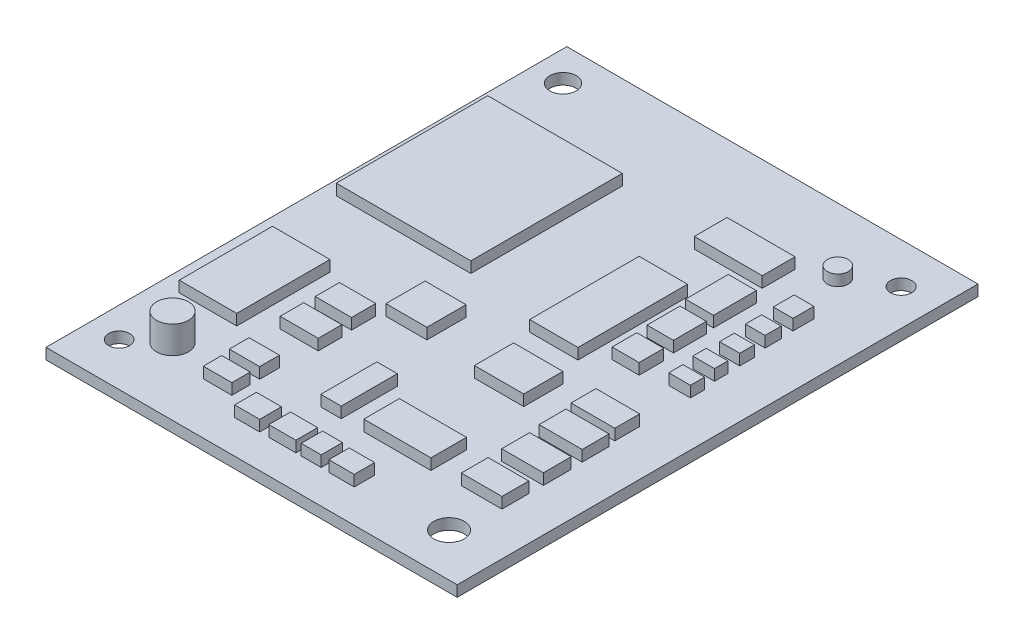
SolidWorks part; units mm, degrees
ref_plane "Front Plane" through (0, 0, 0) normal (0, 0, 1) x (1, 0, 0)
ref_plane "Top Plane" through (0, 0, 0) normal (0, 1, 0) x (1, 0, 0)
ref_plane "Right Plane" through (0, 0, 0) normal (1, 0, 0) x (0, 0, -1)
sketch "Sketch1" plane through (0, 0, 0) normal (0, 1, 0) x (1, 0, 0)
  line L1 (-15, 19) -> (15, 19)
  line L2 (-15, 19) -> (-15, -19)
  line L3 (-15, -19) -> (15, -19)
  line L4 (15, 19) -> (15, -19)
  line L5 (-15, 19) -> (15, -19) construction
  line L6 (-15, -19) -> (15, 19) construction
  point P0 (0, 0)
  dimension "D1" = 30
  dimension "D2" = 38
extrude "Boss-Extrude1" add sketch "Sketch1" along normal blind 0.8
sketch "Sketch2" plane through (0, 0.8, 0) normal (0, 1, 0) x (1, 0, 0)
  circle A0 centre (11.2507, -15.8422) radius 1.1091
  circle A1 centre (-12.8224, -15.8422) radius 0.767
  circle A2 centre (12.3598, 16.0288) radius 0.7754
  circle A3 centre (-12.8224, 16.5455) radius 0.9653
extrude "Cut-Extrude1" cut sketch "Sketch2" against normal blind 0.8
sketch "Sketch3" plane through (0, 0.8, 0) normal (0, 1, 0) x (1, 0, 0)
  line L1 (1.93, -10.1482) -> (6.8248, -10.1482)
  line L2 (1.93, -10.1482) -> (1.93, -12.7419)
  line L3 (1.93, -12.7419) -> (6.8248, -12.7419)
  line L4 (6.8248, -10.1482) -> (6.8248, -12.7419)
  line L5 (1.93, -10.1482) -> (6.8248, -12.7419) construction
  line L6 (1.93, -12.7419) -> (6.8248, -10.1482) construction
  line L7 (-13.5845, -3.8908) -> (-9.3917, -3.8908)
  line L8 (-13.5845, -3.8908) -> (-13.5845, -10.6955)
  line L9 (-13.5845, -10.6955) -> (-9.3917, -10.6955)
  line L10 (-9.3917, -3.8908) -> (-9.3917, -10.6955)
  line L11 (-13.5845, -3.8908) -> (-9.3917, -10.6955) construction
  line L12 (-13.5845, -10.6955) -> (-9.3917, -3.8908) construction
  line L13 (2.5786, -2.4623) -> (6.1761, -2.4623)
  line L14 (2.5786, -2.4623) -> (2.5786, -5.3193)
  line L15 (2.5786, -5.3193) -> (6.1761, -5.3193)
  line L16 (6.1761, -2.4623) -> (6.1761, -5.3193)
  line L17 (2.5786, -2.4623) -> (6.1761, -5.3193) construction
  line L18 (2.5786, -5.3193) -> (6.1761, -2.4623) construction
  line L19 (1.6859, 7.5904) -> (5.2143, 7.5904)
  line L20 (1.6859, 7.5904) -> (1.6859, -0.3999)
  line L21 (1.6859, -0.3999) -> (5.2143, -0.3999)
  line L22 (5.2143, 7.5904) -> (5.2143, -0.3999)
  line L23 (1.6859, 7.5904) -> (5.2143, -0.3999) construction
  line L24 (1.6859, -0.3999) -> (5.2143, 7.5904) construction
  line L25 (2.4412, 13.249) -> (7.4016, 13.249)
  line L26 (2.4412, 13.249) -> (2.4412, 10.857)
  line L27 (2.4412, 10.857) -> (7.4016, 10.857)
  line L28 (7.4016, 13.249) -> (7.4016, 10.857)
  line L29 (2.4412, 13.249) -> (7.4016, 10.857) construction
  line L30 (2.4412, 10.857) -> (7.4016, 13.249) construction
  line L31 (-7.5907, -5.0005) -> (-4.9407, -5.0005)
  line L32 (-7.5907, -5.0005) -> (-7.5907, -6.7672)
  line L33 (-7.5907, -6.7672) -> (-4.9407, -6.7672)
  line L34 (-4.9407, -5.0005) -> (-4.9407, -6.7672)
  line L35 (-7.5907, -5.0005) -> (-4.9407, -6.7672) construction
  line L36 (-7.5907, -6.7672) -> (-4.9407, -5.0005) construction
  line L37 (-7.6193, -7.5766) -> (-4.841, -7.5766)
  line L38 (-7.6193, -7.5766) -> (-7.6193, -9.2961)
  line L39 (-7.6193, -9.2961) -> (-4.841, -9.2961)
  line L40 (-4.841, -7.5766) -> (-4.841, -9.2961)
  line L41 (-7.6193, -7.5766) -> (-4.841, -9.2961) construction
  line L42 (-7.6193, -9.2961) -> (-4.841, -7.5766) construction
  line L43 (-1.2109, -8.6492) -> (0.2813, -8.6492)
  line L44 (-1.2109, -8.6492) -> (-1.2109, -12.7419)
  line L45 (-1.2109, -12.7419) -> (0.2813, -12.7419)
  line L46 (0.2813, -8.6492) -> (0.2813, -12.7419)
  line L47 (-1.2109, -8.6492) -> (0.2813, -12.7419) construction
  line L48 (-1.2109, -12.7419) -> (0.2813, -8.6492) construction
  line L49 (-7.4035, -11.7825) -> (-5.189, -11.7825)
  line L50 (-7.4035, -11.7825) -> (-7.4035, -13.2229)
  line L51 (-7.4035, -13.2229) -> (-5.189, -13.2229)
  line L52 (-5.189, -11.7825) -> (-5.189, -13.2229)
  line L53 (-7.4035, -11.7825) -> (-5.189, -13.2229) construction
  line L54 (-7.4035, -13.2229) -> (-5.189, -11.7825) construction
  line L55 (-7.2713, -13.9088) -> (-5.189, -13.9088)
  line L56 (-7.2713, -13.9088) -> (-7.2713, -15.2524)
  line L57 (-7.2713, -15.2524) -> (-5.189, -15.2524)
  line L58 (-5.189, -13.9088) -> (-5.189, -15.2524)
  line L59 (-7.2713, -13.9088) -> (-5.189, -15.2524) construction
  line L60 (-7.2713, -15.2524) -> (-5.189, -13.9088) construction
  line L61 (8.8919, -10.6347) -> (11.8568, -10.6347)
  line L62 (8.8919, -10.6347) -> (8.8919, -12.5892)
  line L63 (8.8919, -12.5892) -> (11.8568, -12.5892)
  line L64 (11.8568, -10.6347) -> (11.8568, -12.5892)
  line L65 (8.8919, -10.6347) -> (11.8568, -12.5892) construction
  line L66 (8.8919, -12.5892) -> (11.8568, -10.6347) construction
  line L67 (8.832, -7.5502) -> (11.872, -7.5502)
  line L68 (8.832, -7.5502) -> (8.832, -9.5816)
  line L69 (8.832, -9.5816) -> (11.872, -9.5816)
  line L70 (11.872, -7.5502) -> (11.872, -9.5816)
  line L71 (8.832, -7.5502) -> (11.872, -9.5816) construction
  line L72 (8.832, -9.5816) -> (11.872, -7.5502) construction
  line L73 (8.6665, -4.7293) -> (11.8136, -4.7293)
  line L74 (8.6665, -4.7293) -> (8.6665, -6.6941)
  line L75 (8.6665, -6.6941) -> (11.8136, -6.6941)
  line L76 (11.8136, -4.7293) -> (11.8136, -6.6941)
  line L77 (8.6665, -4.7293) -> (11.8136, -6.6941) construction
  line L78 (8.6665, -6.6941) -> (11.8136, -4.7293) construction
  line L79 (8.4704, -2.3451) -> (11.6619, -2.3451)
  line L80 (8.4704, -2.3451) -> (8.4704, -4.1633)
  line L81 (8.4704, -4.1633) -> (11.6619, -4.1633)
  line L82 (11.6619, -2.3451) -> (11.6619, -4.1633)
  line L83 (8.4704, -2.3451) -> (11.6619, -4.1633) construction
  line L84 (8.4704, -4.1633) -> (11.6619, -2.3451) construction
  line L85 (10.1264, 2.3454) -> (11.7073, 2.3454)
  line L86 (10.1264, 2.3454) -> (10.1264, 1.3123)
  line L87 (10.1264, 1.3123) -> (11.7073, 1.3123)
  line L88 (11.7073, 2.3454) -> (11.7073, 1.3123)
  line L89 (10.1264, 2.3454) -> (11.7073, 1.3123) construction
  line L90 (10.1264, 1.3123) -> (11.7073, 2.3454) construction
  line L91 (9.9465, 4.2213) -> (11.5322, 4.2213)
  line L92 (9.9465, 4.2213) -> (9.9465, 3.2424)
  line L93 (9.9465, 3.2424) -> (11.5322, 3.2424)
  line L94 (11.5322, 4.2213) -> (11.5322, 3.2424)
  line L95 (9.9465, 4.2213) -> (11.5322, 3.2424) construction
  line L96 (9.9465, 3.2424) -> (11.5322, 4.2213) construction
  line L97 (10.0141, 6.2043) -> (11.4835, 6.2043)
  line L98 (10.0141, 6.2043) -> (10.0141, 5.1318)
  line L99 (10.0141, 5.1318) -> (11.4835, 5.1318)
  line L100 (11.4835, 6.2043) -> (11.4835, 5.1318)
  line L101 (10.0141, 6.2043) -> (11.4835, 5.1318) construction
  line L102 (10.0141, 5.1318) -> (11.4835, 6.2043) construction
  line L103 (9.8442, 8.3653) -> (11.2807, 8.3653)
  line L104 (9.8442, 8.3653) -> (9.8442, 7.1841)
  line L105 (9.8442, 7.1841) -> (11.2807, 7.1841)
  line L106 (11.2807, 8.3653) -> (11.2807, 7.1841)
  line L107 (9.8442, 8.3653) -> (11.2807, 7.1841) construction
  line L108 (9.8442, 7.1841) -> (11.2807, 8.3653) construction
  line L109 (9.7825, 10.8031) -> (11.2191, 10.8031)
  line L110 (9.7825, 10.8031) -> (9.7825, 9.2813)
  line L111 (9.7825, 9.2813) -> (11.2191, 9.2813)
  line L112 (11.2191, 10.8031) -> (11.2191, 9.2813)
  line L113 (9.7825, 10.8031) -> (11.2191, 9.2813) construction
  line L114 (9.7825, 9.2813) -> (11.2191, 10.8031) construction
  line L115 (-13.984, 12.2149) -> (-4.1687, 12.2149)
  line L116 (-13.984, 12.2149) -> (-13.984, 1.1627)
  line L117 (-13.984, 1.1627) -> (-4.1687, 1.1627)
  line L118 (-4.1687, 12.2149) -> (-4.1687, 1.1627)
  line L119 (-13.984, 12.2149) -> (-4.1687, 1.1627) construction
  line L120 (-13.984, 1.1627) -> (-4.1687, 12.2149) construction
  circle A0 centre (9.5146, 14.2572) radius 0.7624
  point P0 (4.3774, -11.4451)
  point P5 (-11.4881, -7.2932)
  point P10 (4.3774, -3.8908)
  point P15 (3.4501, 3.5953)
  point P20 (4.9214, 12.053)
  point P25 (-6.2657, -5.8838)
  point P30 (-6.2302, -8.4363)
  point P35 (-0.4648, -10.6955)
  point P40 (-6.2963, -12.5027)
  point P45 (-6.2302, -14.5806)
  point P50 (10.3743, -11.6119)
  point P55 (10.352, -8.5659)
  point P60 (10.2401, -5.7117)
  point P65 (10.0662, -3.2542)
  point P70 (10.9169, 1.8288)
  point P75 (10.7393, 3.7318)
  point P80 (10.7488, 5.668)
  point P85 (10.5624, 7.7747)
  point P90 (10.5008, 10.0422)
  point P95 (-9.0764, 6.6888)
extrude "Boss-Extrude2" add sketch "Sketch3" along normal blind 0.8
sketch "Sketch4" plane through (0, 0.8, 0) normal (0, 1, 0) x (1, 0, 0)
  line L1 (-3.681, -14.9652) -> (-1.8559, -14.9652)
  line L2 (-3.681, -14.9652) -> (-3.681, -16.555)
  line L3 (-3.681, -16.555) -> (-1.8559, -16.555)
  line L4 (-1.8559, -14.9652) -> (-1.8559, -16.555)
  line L5 (-3.681, -14.9652) -> (-1.8559, -16.555) construction
  line L6 (-3.681, -16.555) -> (-1.8559, -14.9652) construction
  line L7 (-1.1904, -14.9652) -> (0.7852, -14.9652)
  line L8 (-1.1904, -14.9652) -> (-1.1904, -16.555)
  line L9 (-1.1904, -16.555) -> (0.7852, -16.555)
  line L10 (0.7852, -14.9652) -> (0.7852, -16.555)
  line L11 (-1.1904, -14.9652) -> (0.7852, -16.555) construction
  line L12 (-1.1904, -16.555) -> (0.7852, -14.9652) construction
  line L13 (1.1762, -14.9975) -> (2.6312, -14.9975)
  line L14 (1.1762, -14.9975) -> (1.1762, -16.555)
  line L15 (1.1762, -16.555) -> (2.6312, -16.555)
  line L16 (2.6312, -14.9975) -> (2.6312, -16.555)
  line L17 (1.1762, -14.9975) -> (2.6312, -16.555) construction
  line L18 (1.1762, -16.555) -> (2.6312, -14.9975) construction
  line L19 (3.2196, -15.0919) -> (5.0703, -15.0919)
  line L20 (3.2196, -15.0919) -> (3.2196, -16.5824)
  line L21 (3.2196, -16.5824) -> (5.0703, -16.5824)
  line L22 (5.0703, -15.0919) -> (5.0703, -16.5824)
  line L23 (3.2196, -15.0919) -> (5.0703, -16.5824) construction
  line L24 (3.2196, -16.5824) -> (5.0703, -15.0919) construction
  line L25 (6.4306, 2.6738) -> (8.3976, 2.6738)
  line L26 (6.4306, 2.6738) -> (6.4306, 0.8751)
  line L27 (6.4306, 0.8751) -> (8.3976, 0.8751)
  line L28 (8.3976, 2.6738) -> (8.3976, 0.8751)
  line L29 (6.4306, 2.6738) -> (8.3976, 0.8751) construction
  line L30 (6.4306, 0.8751) -> (8.3976, 2.6738) construction
  line L31 (6.3201, 5.9361) -> (8.2474, 5.9361)
  line L32 (6.3201, 5.9361) -> (6.3201, 3.5349)
  line L33 (6.3201, 3.5349) -> (8.2474, 3.5349)
  line L34 (8.2474, 5.9361) -> (8.2474, 3.5349)
  line L35 (6.3201, 5.9361) -> (8.2474, 3.5349) construction
  line L36 (6.3201, 3.5349) -> (8.2474, 5.9361) construction
  line L37 (6.0846, 9.6961) -> (8.1254, 9.6961)
  line L38 (6.0846, 9.6961) -> (6.0846, 6.5729)
  line L39 (6.0846, 6.5729) -> (8.1254, 6.5729)
  line L40 (8.1254, 9.6961) -> (8.1254, 6.5729)
  line L41 (6.0846, 9.6961) -> (8.1254, 6.5729) construction
  line L42 (6.0846, 6.5729) -> (8.1254, 9.6961) construction
  line L43 (-4.5613, -1.7829) -> (-1.571, -1.7829)
  line L44 (-4.5613, -1.7829) -> (-4.5613, -4.6376)
  line L45 (-4.5613, -4.6376) -> (-1.571, -4.6376)
  line L46 (-1.571, -1.7829) -> (-1.571, -4.6376)
  line L47 (-4.5613, -1.7829) -> (-1.571, -4.6376) construction
  line L48 (-4.5613, -4.6376) -> (-1.571, -1.7829) construction
  point P0 (-2.7685, -15.7601)
  point P5 (-0.2026, -15.7601)
  point P10 (1.9037, -15.7763)
  point P15 (4.145, -15.8372)
  point P20 (7.4141, 1.7745)
  point P25 (7.2837, 4.7355)
  point P30 (7.105, 8.1345)
  point P35 (-3.0662, -3.2102)
extrude "Boss-Extrude3" add sketch "Sketch4" along normal blind 0.8
sketch "Sketch5" plane through (0, 0.8, 0) normal (0, 1, 0) x (1, 0, 0)
  circle A0 centre (-10.678, -14.0917) radius 1.1662
extrude "Boss-Extrude4" add sketch "Sketch5" along normal blind 2
